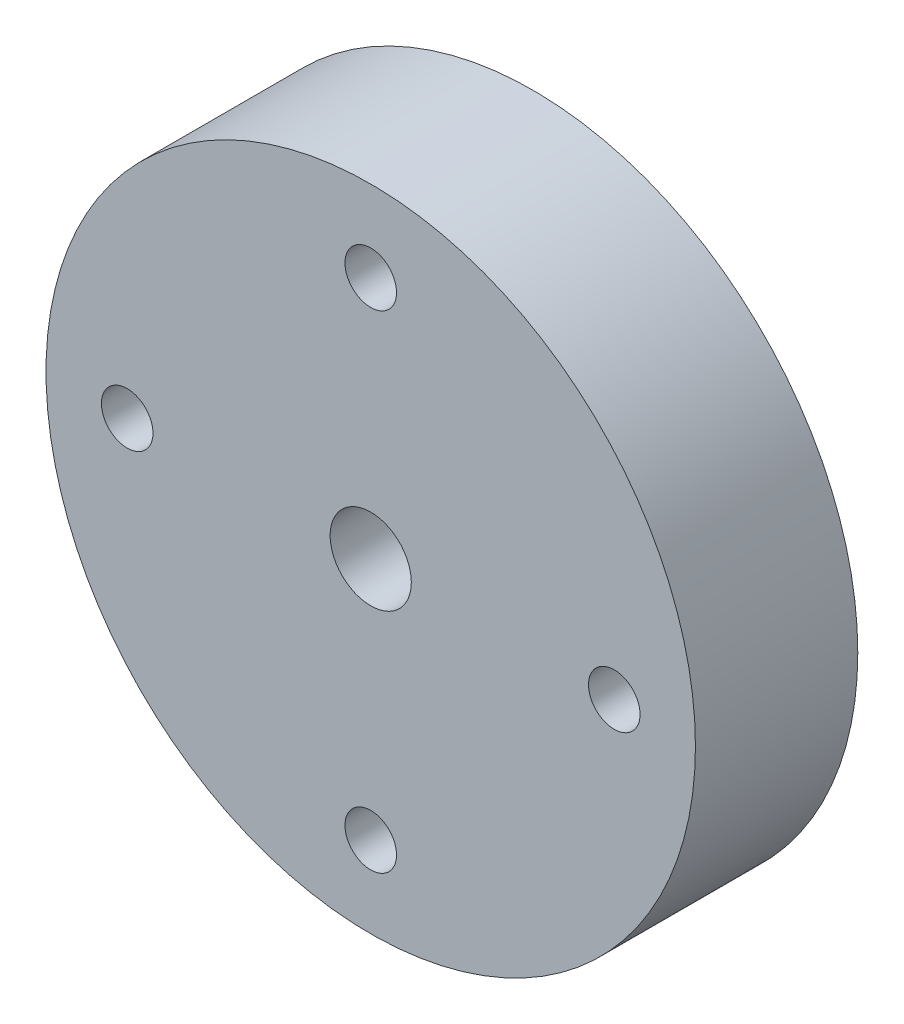
SolidWorks part; units mm, degrees
material "6061 Alloy"
ref_plane "Front Plane" through (0, 0, 0) normal (0, 0, 1) x (1, 0, 0)
ref_plane "Top Plane" through (0, 0, 0) normal (0, 1, 0) x (1, 0, 0)
ref_plane "Right Plane" through (0, 0, 0) normal (1, 0, 0) x (0, 0, -1)
sketch "Sketch3" plane through (0, 0, 0) normal (0, 0, 1) x (1, 0, 0)
  circle A0 centre (0, 0) radius 20
  circle A1 centre (0, 0) radius 2.5
  point P37 (0, 0)
  dimension "D1" = 40
  dimension "D2" = 5
extrude "Boss-Extrude2" add sketch "Sketch3" along normal blind 10
hole_wizard "1/8 (0.125) Diameter Hole2" positions "Sketch4" profile "Sketch5" hole size "1/8" standard "ANSI Inch" end condition up to next
sketch "Sketch4" plane through (0, 0, 10) normal (0, 0, 1) x (1, 0, 0)
  point P0 (0, 15)
  point P17 (15, 0)
  point P18 (0, -15)
  point P19 (-15, 0)
  dimension "D1" = 4
  dimension "D2" = 15
sketch "Sketch5" plane through (0, 15, 10) normal (1, 0, 0) x (0, -1, 0)
  line L0 (0, 0) -> (0, 10)
  line L1 (0, 10) -> (1.5875, 10)
  line L2 (1.5875, 10) -> (1.5875, 0)
  line L5 (1.5875, 0) -> (0, 0)
  line L11 (0, -6.35) -> (0, 107.95) construction
  dimension "Thru Hole Dia." = 3.175
  dimension "Thru Hole Depth" = 10
